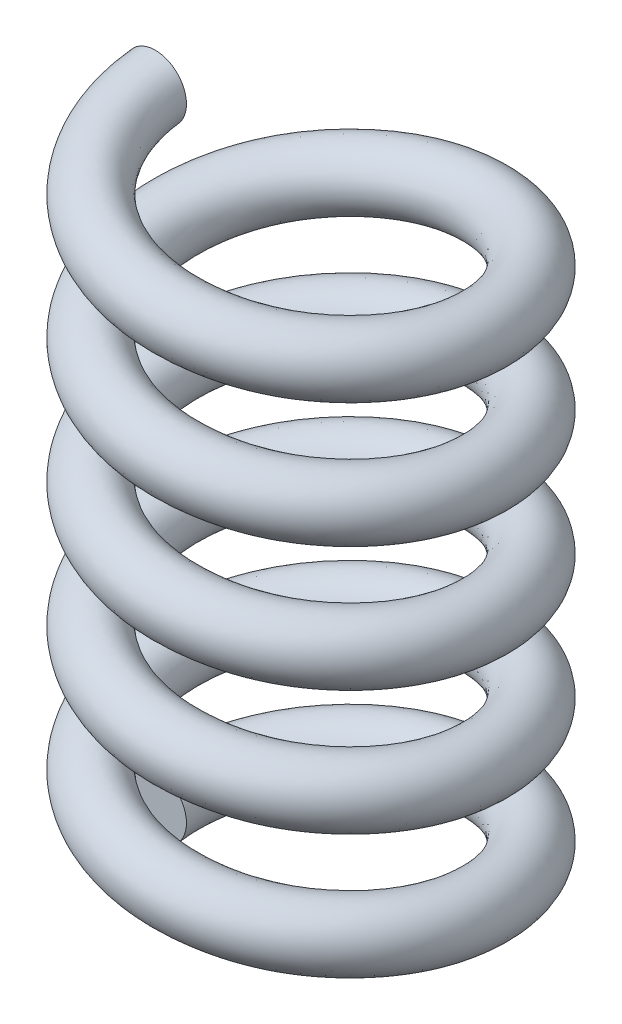
SolidWorks part; units mm, degrees
ref_plane "Front Plane" through (0, 0, 0) normal (0, 0, 1) x (1, 0, 0)
ref_plane "Top Plane" through (0, 0, 0) normal (0, 1, 0) x (1, 0, 0)
ref_plane "Right Plane" through (0, 0, 0) normal (1, 0, 0) x (0, 0, -1)
sketch "Sketch1" plane through (0, 0, 0) normal (0, 1, 0) x (1, 0, 0)
  circle A0 centre (0, 0) radius 2
  dimension "D1" = 4
curve "Helix/Spiral1"
sketch "Sketch2" plane through (0, 0, 0) normal (0, 0, 1) x (1, 0, 0)
  circle A0 centre (-2, 0) radius 0.4
  spline S0 degree 3 poles (-2, 0) (-2, 0.0331) (-1.8959, 0.1001) (-1.451, 0.2) (-0.7853, 0.3) (0, 0.4) (0.7853, 0.5) (1.451, 0.6) (1.8959, 0.7) (2.0521, 0.8) (1.8959, 0.9) (1.451, 1) (0.7853, 1.1) (0, 1.2) (-0.7853, 1.3) (-1.451, 1.4) (-1.8959, 1.5) (-2.0521, 1.6) (-1.8959, 1.7) (-1.451, 1.8) (-0.7853, 1.9) (0, 2) (0.7853, 2.1) (1.451, 2.2) (1.8959, 2.3) (2.0521, 2.4) (1.8959, 2.5) (1.451, 2.6) (0.7853, 2.7) (0, 2.8) (-0.7853, 2.9) (-1.451, 3) (-1.8959, 3.1) (-2.0521, 3.2) (-1.8959, 3.3) (-1.451, 3.4) (-0.7853, 3.5) (0, 3.6) (0.7853, 3.7) (1.451, 3.8) (1.8959, 3.9) (2.0521, 4) (1.8959, 4.1) (1.451, 4.2) (0.7853, 4.3) (0, 4.4) (-0.7853, 4.5) (-1.451, 4.6) (-1.8959, 4.7) (-2.0521, 4.8) (-1.8959, 4.9) (-1.451, 5) (-0.7853, 5.1) (0, 5.2) (0.7853, 5.3) (1.451, 5.4) (1.8959, 5.5) (2.0521, 5.6) (1.8959, 5.7) (1.451, 5.8) (0.7853, 5.9) (0, 6) (-0.7853, 6.1) (-1.451, 6.2) (-1.8959, 6.3) (-2.0521, 6.4) (-1.8959, 6.5) (-1.451, 6.6) (-0.7853, 6.7) (0, 6.8) (0.7853, 6.9) (1.451, 7) (1.8959, 7.1) (2.0521, 7.2) (1.8959, 7.3) (1.451, 7.4) (0.7853, 7.5) (0, 7.6) (-0.7853, 7.7) (-1.451, 7.8) (-1.8959, 7.8999) (-2, 7.9669) (-2, 8) knots 0 0 0 0 0.0125 0.025 0.0375 0.05 0.0625 0.075 0.0875 0.1 0.1125 0.125 0.1375 0.15 0.1625 0.175 0.1875 0.2 0.2125 0.225 0.2375 0.25 0.2625 0.275 0.2875 0.3 0.3125 0.325 0.3375 0.35 0.3625 0.375 0.3875 0.4 0.4125 0.425 0.4375 0.45 0.4625 0.475 0.4875 0.5 0.5125 0.525 0.5375 0.55 0.5625 0.575 0.5875 0.6 0.6125 0.625 0.6375 0.65 0.6625 0.675 0.6875 0.7 0.7125 0.725 0.7375 0.75 0.7625 0.775 0.7875 0.8 0.8125 0.825 0.8375 0.85 0.8625 0.875 0.8875 0.9 0.9125 0.925 0.9375 0.95 0.9625 0.975 0.9875 1 1 1 1 construction
  dimension "D1" = 0.8
sweep "Sweep1" add profiles "Sketch2" path "Helix/Spiral1"
ref_plane "Plane1" through (0, 8, 0) normal (0, 1, 0) x (1, 0, 0)
